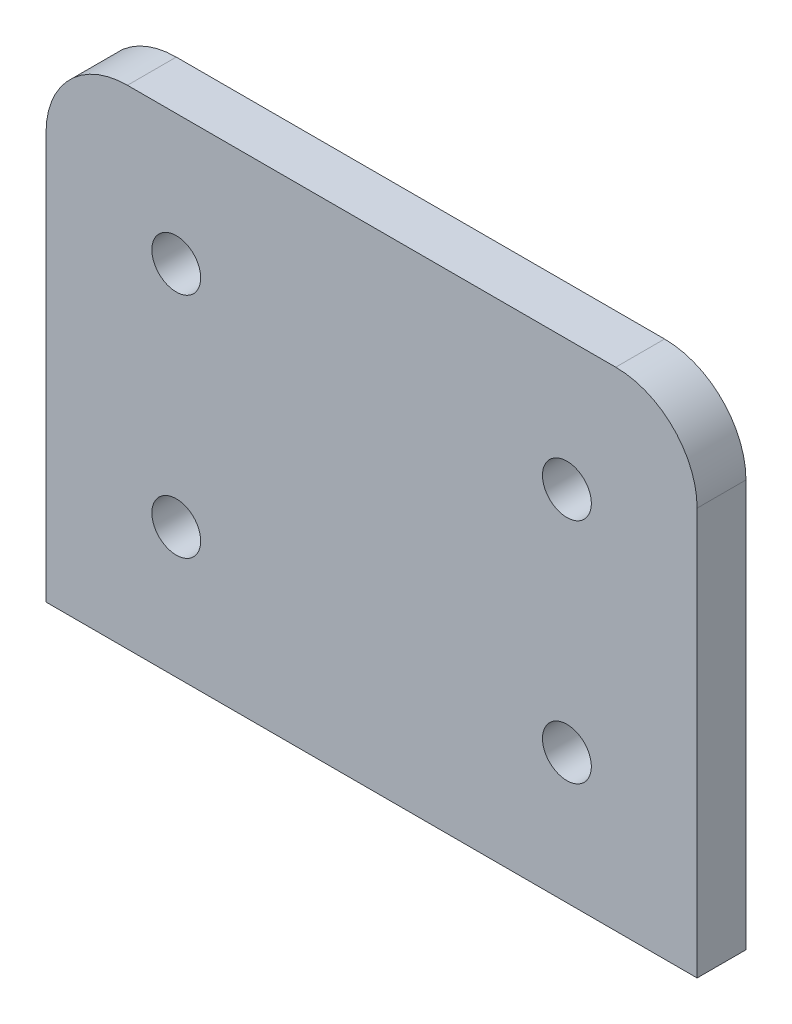
SolidWorks part; units mm, degrees
ref_plane "前基準面" through (0, 0, 0) normal (0, 0, 1) x (1, 0, 0)
ref_plane "上基準面" through (0, 0, 0) normal (0, 1, 0) x (1, 0, 0)
ref_plane "右基準面" through (0, 0, 0) normal (1, 0, 0) x (0, 0, -1)
sketch "草圖1" plane through (0, 0, 0) normal (0, 0, 1) x (1, 0, 0)
  line L0 (0, 0) -> (0, 23.2697) construction
  line L1 (-20, 15) -> (20, 15)
  line L2 (-20, 15) -> (-20, -15)
  line L3 (-20, -15) -> (20, -15)
  line L4 (20, 15) -> (20, -15)
  line L5 (-20, 15) -> (20, -15) construction
  line L6 (-20, -15) -> (20, 15) construction
  circle A0 centre (-12, 7) radius 1.5
  circle A1 centre (-12, -7) radius 1.5
  circle A2 centre (12, -7) radius 1.5
  circle A3 centre (12, 7) radius 1.5
  point P0 (0, 0)
  dimension "D5" = 3
  dimension "D1" = 30
  dimension "D2" = 40
  dimension "D3" = 8
  dimension "D4" = 8
  dimension "D6" = 8
extrude "填料-伸長1" add sketch "草圖1" along normal blind 3
fillet "圓角1" radius 5 2 edges at (20, 15, 1.5) (-20, 15, 1.5)
